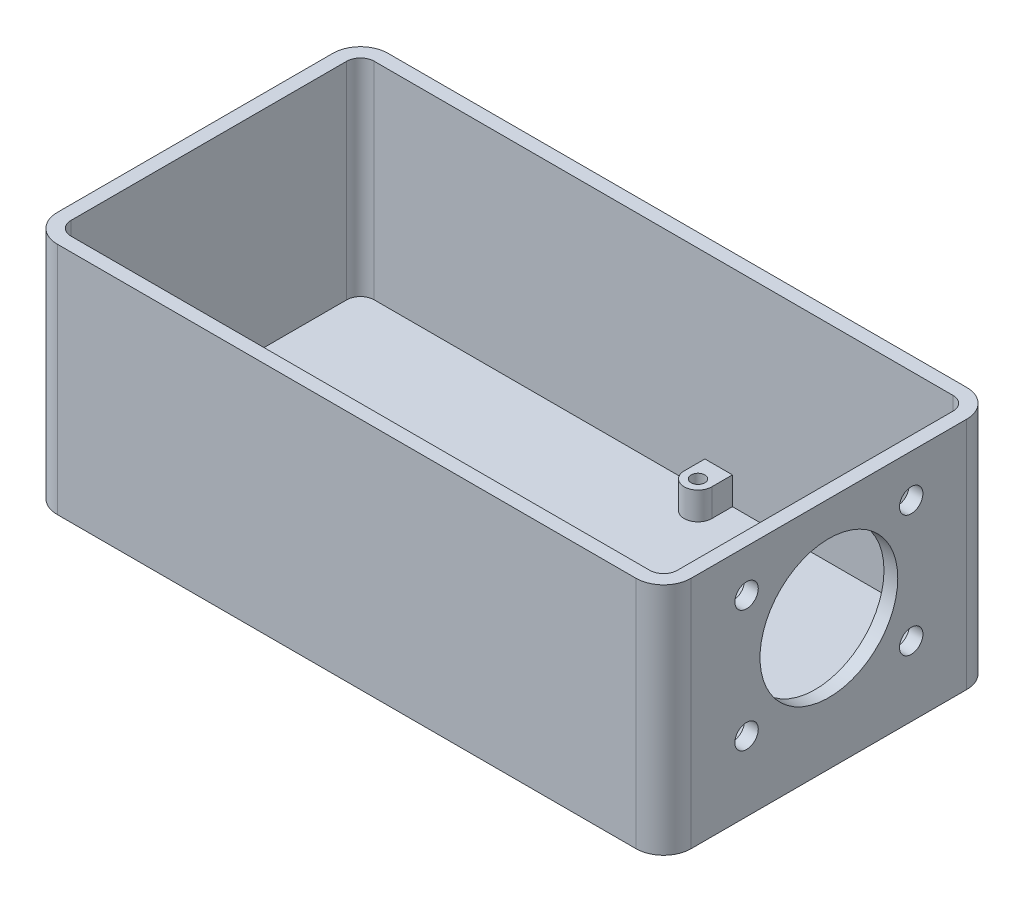
SolidWorks part; units mm, degrees
ref_plane "Front Plane" through (0, 0, 0) normal (0, 0, 1) x (1, 0, 0)
ref_plane "Top Plane" through (0, 0, 0) normal (0, 1, 0) x (1, 0, 0)
ref_plane "Right Plane" through (0, 0, 0) normal (1, 0, 0) x (0, 0, -1)
sketch "Sketch1" plane through (0, 0, 0) normal (0, 1, 0) x (1, 0, 0)
  line L1 (0, 0) -> (116.84, 0)
  line L2 (0, 0) -> (0, 86.36)
  line L3 (0, 86.36) -> (116.84, 86.36)
  line L4 (116.84, 0) -> (116.84, 86.36)
  dimension "D1" = 116.84
  dimension "D2" = 86.36
extrude "Boss-Extrude2" add sketch "Sketch1" along normal blind 5.08
fillet "Fillet1" radius 12.7 4 edges at (0, 2.54, -86.36) (116.84, 2.54, -86.36) (116.84, 2.54, 0) (0, 2.54, 0)
sketch "Sketch3" plane through (0, 5.08, 0) normal (0, 1, 0) x (1, 0, 0)
  line L1 (0, 73.66) -> (116.84, 73.66)
  line L2 (0, 73.66) -> (0, 12.7)
  line L3 (0, 12.7) -> (116.84, 12.7)
  line L4 (116.84, 73.66) -> (116.84, 12.7)
  line L5 (2.54, 71.12) -> (114.3, 71.12)
  line L6 (2.54, 71.12) -> (2.54, 15.24)
  line L7 (2.54, 15.24) -> (114.3, 15.24)
  line L8 (114.3, 71.12) -> (114.3, 15.24)
  dimension "D1" = 2.54
  dimension "D2" = 2.54
  dimension "D3" = 2.54
  dimension "D4" = 2.54
extrude "Boss-Extrude3" add sketch "Sketch3" along normal blind 38.1
sketch "Sketch4" plane through (0, 5.08, 0) normal (0, 1, 0) x (1, 0, 0)
  line L0 (58.42, 71.12) -> (58.42, 15.24) construction
  line L1 (2.54, 71.12) -> (12.7, 71.12)
  line L2 (2.54, 71.12) -> (2.54, 60.96)
  line L3 (2.54, 60.96) -> (12.7, 60.96)
  line L4 (12.7, 71.12) -> (12.7, 60.96)
  line L5 (114.3, 71.12) -> (2.54, 71.12) construction
  line L6 (2.54, 15.24) -> (114.3, 15.24) construction
  line L7 (114.3, 43.18) -> (2.54, 43.18) construction
  line L8 (114.3, 15.24) -> (114.3, 71.12) construction
  line L9 (2.54, 71.12) -> (2.54, 15.24) construction
  line L10 (104.14, 71.12) -> (104.14, 60.96)
  line L11 (114.3, 60.96) -> (104.14, 60.96)
  line L12 (114.3, 71.12) -> (114.3, 60.96)
  line L13 (114.3, 71.12) -> (104.14, 71.12)
  line L14 (114.3, 15.24) -> (104.14, 15.24)
  line L15 (114.3, 15.24) -> (114.3, 25.4)
  line L16 (114.3, 25.4) -> (104.14, 25.4)
  line L17 (104.14, 15.24) -> (104.14, 25.4)
  line L18 (12.7, 15.24) -> (12.7, 25.4)
  line L19 (2.54, 25.4) -> (12.7, 25.4)
  line L20 (2.54, 15.24) -> (2.54, 25.4)
  line L21 (2.54, 15.24) -> (12.7, 15.24)
  dimension "D1" = 10.16
  dimension "D2" = 10.16
extrude "Boss-Extrude5" add sketch "Sketch4" along normal blind 34.29
fillet "Fillet3" radius 5.08 4 edges at (104.14, 22.225, -25.4) (12.7, 22.225, -25.4) (104.14, 22.225, -60.96) (12.7, 22.225, -60.96)
sketch "Sketch5" plane through (0, 39.37, 0) normal (0, 1, 0) x (1, 0, 0)
  circle A0 centre (7.62, 66.04) radius 1.27
  circle A1 centre (109.22, 66.04) radius 1.27
  circle A2 centre (109.22, 20.32) radius 1.27
  circle A3 centre (7.62, 20.32) radius 1.27
  dimension "D1" = 2.54
  dimension "D2" = 2.54
  dimension "D3" = 2.54
  dimension "D4" = 2.54
extrude "Cut-Extrude1" cut sketch "Sketch5" against normal blind 34.29
sketch "Sketch6" plane through (0, 5.08, 0) normal (0, 1, 0) x (1, 0, 0)
  line L1 (0, 73.66) -> (116.84, 73.66)
  line L2 (0, 73.66) -> (0, 12.7)
  line L3 (0, 12.7) -> (116.84, 12.7)
  line L4 (116.84, 73.66) -> (116.84, 12.7)
  line L5 (-31.6252, 119.5269) -> (166.8323, 119.5269)
  line L6 (-31.6252, 119.5269) -> (-31.6252, -30.2876)
  line L7 (-31.6252, -30.2876) -> (166.8323, -30.2876)
  line L8 (166.8323, 119.5269) -> (166.8323, -30.2876)
extrude "Cut-Extrude2" cut sketch "Sketch6" against normal up to next
fillet "Fillet6" radius 5.08 4 edges at (0, 21.59, -73.66) (116.84, 21.59, -73.66) (116.84, 21.59, -12.7) (0, 21.59, -12.7)
sketch "Sketch7" plane through (116.84, 0, 0) normal (1, 0, 0) x (0, 0, -1)
  circle A0 centre (43.18, 24.13) radius 12.7
  circle A1 centre (28.0035, 35.3568) radius 2.159
  circle A2 centre (58.3565, 35.3568) radius 2.159
  circle A3 centre (28.0035, 12.9032) radius 2.159
  circle A4 centre (58.3565, 12.9032) radius 2.159
  dimension "D1" = 25.4
  dimension "D3" = 4.318
  dimension "D4" = 4.318
  dimension "D5" = 4.318
  dimension "D6" = 4.318
  dimension "D2" = 19.05
  dimension "D7" = 25.4
  dimension "D8" = 15.1765
  dimension "D9" = 15.1765
  dimension "D10" = 11.2268
  dimension "D11" = 11.2268
extrude "Cut-Extrude3" cut sketch "Sketch7" against normal up to next
sketch "Sketch8" plane through (0, 0, 0) normal (-1, 0, 0) x (0, 0, 1)
  circle A0 centre (-43.18, 10.16) radius 3.175
  dimension "D3" = 6.35
  dimension "D1" = 25.4
  dimension "D2" = 10.16
extrude "Cut-Extrude4" cut sketch "Sketch8" against normal up to next
sketch "Sketch10" plane through (0, 5.08, 0) normal (0, 1, 0) x (1, 0, 0)
  line L0 (69.85, 19.05) -> (69.85, 15.24)
  line L1 (12.7, 15.24) -> (104.14, 15.24) construction
  line L2 (69.85, 15.24) -> (64.77, 15.24)
  line L3 (64.77, 15.24) -> (64.77, 19.05)
  line L4 (71.12, 67.31) -> (71.12, 71.12)
  line L5 (104.14, 71.12) -> (12.7, 71.12) construction
  line L6 (71.12, 71.12) -> (66.04, 71.12)
  line L7 (66.04, 71.12) -> (66.04, 67.31)
  arc A0 (69.85, 19.05) -> (64.77, 19.05) centre (67.31, 19.05) ccw
  arc A1 (66.04, 67.31) -> (71.12, 67.31) centre (68.58, 67.31) ccw
  dimension "D1" = 5.08
  dimension "D2" = 5.08
  dimension "D3" = 48.26
  dimension "D4" = 3.81
  dimension "D5" = 36.83
  dimension "D6" = 1.27
extrude "Boss-Extrude9" add sketch "Sketch10" along normal blind 5.08
sketch "Sketch14" plane through (0, 10.16, 0) normal (0, 1, 0) x (1, 0, 0)
  circle A0 centre (67.31, 19.05) radius 1.27
  circle A1 centre (68.58, 67.31) radius 1.27
  dimension "D1" = 2.54
  dimension "D2" = 2.54
extrude "Cut-Extrude6" cut sketch "Sketch14" against normal blind 8.89
sketch "Sketch15" plane through (0, 5.08, 0) normal (0, 1, 0) x (1, 0, 0)
  line L0 (26.67, 33.02) -> (26.67, 35.56) construction
  line L1 (21.59, 33.02) -> (21.59, 35.56)
  line L2 (31.75, 33.02) -> (31.75, 35.56)
  arc A0 (21.59, 33.02) -> (31.75, 33.02) centre (26.67, 33.02) ccw
  arc A1 (31.75, 35.56) -> (21.59, 35.56) centre (26.67, 35.56) ccw
  point P2 (26.67, 34.29)
  dimension "D1" = 7.62
  dimension "D2" = 25.4
  dimension "D3" = 38.1
  dimension "D4" = 5.08
sketch "Sketch21" plane through (0, 39.37, 0) normal (0, 1, 0) x (1, 0, 0)
  line L1 (114.3, 15.24) -> (2.54, 15.24)
  line L2 (114.3, 15.24) -> (114.3, 71.12)
  line L3 (114.3, 71.12) -> (2.54, 71.12)
  line L4 (2.54, 15.24) -> (2.54, 71.12)
extrude "Cut-Extrude7" cut sketch "Sketch21" against normal blind 29.21
sketch "Sketch22" plane through (0, 10.16, 0) normal (0, 1, 0) x (1, 0, 0)
  line L1 (114.3, 15.24) -> (93.3755, 15.24)
  line L2 (114.3, 15.24) -> (114.3, 27.716)
  line L3 (114.3, 27.716) -> (93.3755, 27.716)
  line L4 (93.3755, 15.24) -> (93.3755, 27.716)
  line L5 (114.3, 71.12) -> (98.6818, 71.12)
  line L6 (114.3, 71.12) -> (114.3, 56.93)
  line L7 (114.3, 56.93) -> (98.6818, 56.93)
  line L8 (98.6818, 71.12) -> (98.6818, 56.93)
  line L9 (2.54, 15.24) -> (18.6503, 15.24)
  line L10 (2.54, 15.24) -> (2.54, 29.116)
  line L11 (2.54, 29.116) -> (18.6503, 29.116)
  line L12 (18.6503, 15.24) -> (18.6503, 29.116)
  line L13 (2.54, 71.12) -> (14.5855, 71.12)
  line L14 (2.54, 71.12) -> (2.54, 56.93)
  line L15 (2.54, 56.93) -> (14.5855, 56.93)
  line L16 (14.5855, 71.12) -> (14.5855, 56.93)
extrude "Cut-Extrude8" cut sketch "Sketch22" against normal blind 5.08
fillet "Fillet7" radius 2.54 4 edges at (2.54, 24.13, -71.12) (114.3, 24.13, -71.12) (2.54, 24.13, -15.24) (114.3, 24.13, -15.24)
extrude "Boss-Extrude10" add sketch "Sketch15" along normal blind 5.08
